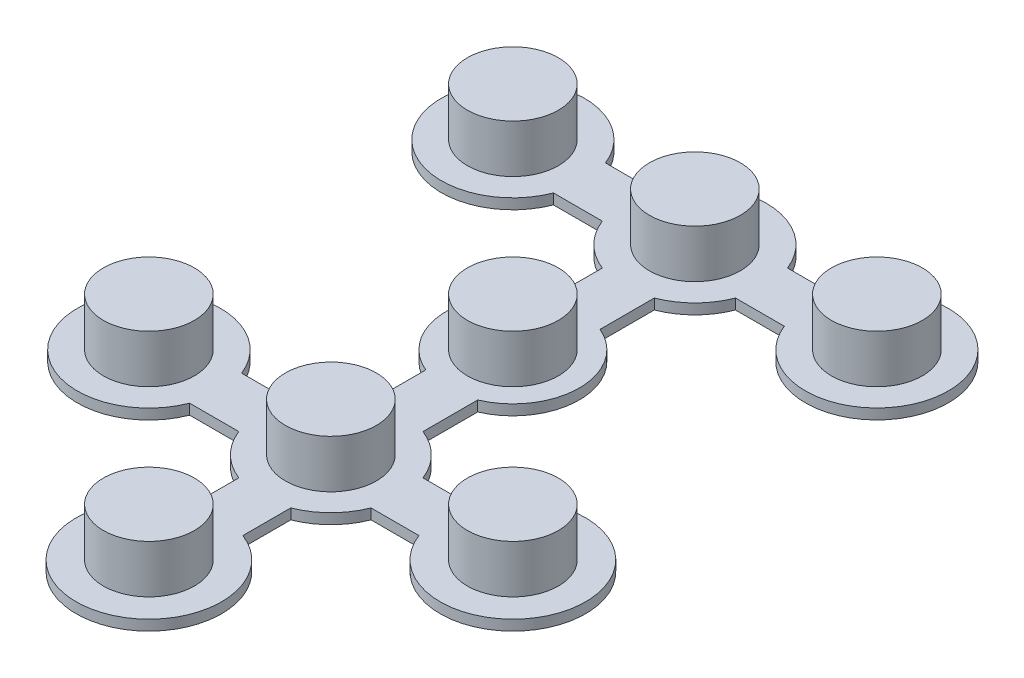
SolidWorks part; units mm, degrees
ref_plane "Front Plane" through (0, 0, 0) normal (0, 0, 1) x (1, 0, 0)
ref_plane "Top Plane" through (0, 0, 0) normal (0, 1, 0) x (1, 0, 0)
ref_plane "Right Plane" through (0, 0, 0) normal (1, 0, 0) x (0, 0, -1)
sketch "Sketch1" plane through (0, 0, 0) normal (0, 1, 0) x (1, 0, 0)
  line L0 (2.5617, 1) -> (4.4383, 1)
  line L1 (4.4383, -1) -> (2.5617, -1)
  line L2 (6, -2.5617) -> (6, -4.6476)
  line L4 (8, -18.3863) -> (8, -16.5433)
  line L5 (2.5662, -13) -> (4.4567, -13)
  line L6 (4.4567, -15) -> (2.5662, -15)
  line L7 (11.3863, -15) -> (9.5433, -15)
  line L8 (9.5617, -1) -> (11.4383, -1)
  line L9 (9.5617, 1) -> (11.4383, 1)
  line L10 (6, -9.3524) -> (6, -11.4567)
  line L11 (8, -4.6476) -> (8, -2.5617)
  line L12 (9.5433, -13) -> (11.3863, -13)
  line L13 (6, -16.5433) -> (6, -18.3863)
  line L14 (8, -11.4567) -> (8, -9.3524)
  arc A0 (2.5617, 1) -> (2.5617, -1) centre (0, 0) ccw
  arc A1 (4.4383, -1) -> (6, -2.5617) centre (7, 0) ccw
  arc A2 (11.4383, -1) -> (11.4383, 1) centre (14, 0) ccw
  arc A3 (6, -4.6476) -> (6, -9.3524) centre (7, -7) ccw
  arc A4 (6, -11.4567) -> (4.4567, -13) centre (7, -14) ccw
  arc A5 (6, -18.3863) -> (8, -18.3863) centre (7, -21) ccw
  arc A6 (2.5662, -13) -> (2.5662, -15) centre (0, -14) ccw
  arc A7 (11.3863, -15) -> (11.3863, -13) centre (14, -14) ccw
  arc A8 (9.5617, 1) -> (4.4383, 1) centre (7, 0) ccw
  arc A9 (8, -2.5617) -> (9.5617, -1) centre (7, 0) ccw
  arc A10 (8, -9.3524) -> (8, -4.6476) centre (7, -7) ccw
  arc A11 (9.5433, -13) -> (8, -11.4567) centre (7, -14) ccw
  arc A12 (4.4567, -15) -> (6, -16.5433) centre (7, -14) ccw
  arc A13 (8, -16.5433) -> (9.5433, -15) centre (7, -14) ccw
  dimension "D1" = 5.5
  dimension "D2" = 2
  dimension "D3" = 7
  dimension "D4" = 7
  dimension "D5" = 7
  dimension "D6" = 7
  dimension "D7" = 7
  dimension "D8" = 2
  dimension "D9" = 2
extrude "Boss-Extrude1" add sketch "Sketch1" along normal blind 0.4
sketch "Sketch2" plane through (0, 0.4, 0) normal (0, 1, 0) x (1, 0, 0)
  circle A0 centre (0, 0) radius 1.75
  circle A1 centre (7, 0) radius 1.75
  circle A2 centre (14, 0) radius 1.75
  circle A3 centre (7, -7) radius 1.75
  circle A4 centre (7, -14) radius 1.75
  circle A5 centre (14, -14) radius 1.75
  circle A6 centre (0, -14) radius 1.75
  circle A7 centre (7, -21) radius 1.75
  dimension "D1" = 3.5
extrude "Boss-Extrude2" add sketch "Sketch2" along normal blind 1.85
